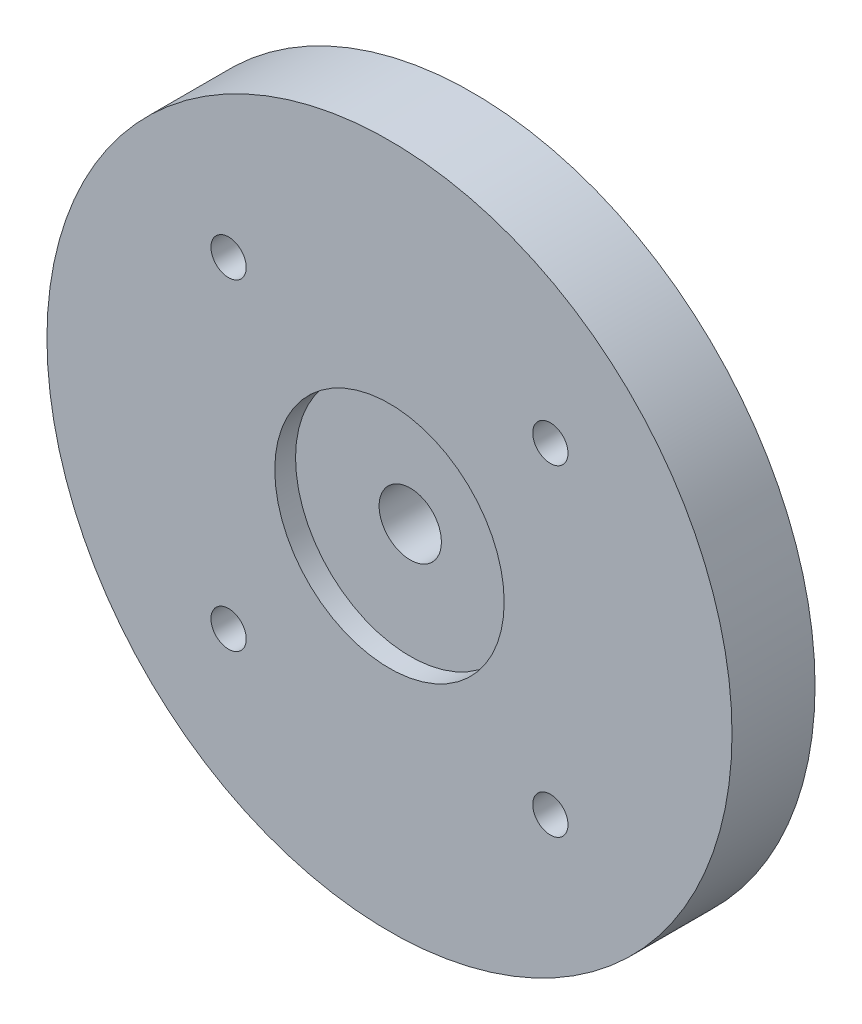
SolidWorks part; units mm, degrees
ref_plane "Front Plane" through (0, 0, 0) normal (0, 0, 1) x (1, 0, 0)
ref_plane "Top Plane" through (0, 0, 0) normal (0, 1, 0) x (1, 0, 0)
ref_plane "Right Plane" through (0, 0, 0) normal (1, 0, 0) x (0, 0, -1)
sketch "Sketch2" plane through (0, 0, 0) normal (0, 0, 1) x (1, 0, 0)
  circle A0 centre (0, 0) radius 33
  dimension "D1" = 66
extrude "Boss-Extrude1" add sketch "Sketch2" along normal blind 8
sketch "Sketch6" plane through (0, 0, 0) normal (0, 0, -1) x (-1, 0, 0)
  circle A0 centre (0, 0) radius 10
  dimension "D1" = 20
extrude "Boss-Extrude2" add sketch "Sketch6" along normal blind 2
sketch "Sketch3" plane through (0, 0, 8) normal (0, 0, 1) x (1, 0, 0)
  line L0 (0, -15.5) -> (0, 15.5) construction
  line L1 (15.5, 15.5) -> (-15.5, 15.5) construction
  line L2 (15.5, -15.5) -> (-15.5, -15.5) construction
  circle A0 centre (-15.5, 15.5) radius 1.7
  circle A1 centre (15.5, 15.5) radius 1.7
  circle A2 centre (15.5, -15.5) radius 1.7
  circle A3 centre (-15.5, -15.5) radius 1.7
  circle A4 centre (0, 0) radius 3
  point P12 (0, 0)
  point P16 (0, 15.5)
  point P19 (0, -15.5)
  dimension "D1" = 3.4
  dimension "D2" = 3.4
  dimension "D3" = 3.4
  dimension "D4" = 3.4
  dimension "D8" = 6
  dimension "D5" = 31
  dimension "D6" = 31
  dimension "D7" = 31
extrude "Cut-Extrude1" cut sketch "Sketch3" against normal through all both and the other way through all
sketch "Sketch4" plane through (0, 0, 0) normal (0, 0, -1) x (-1, 0, 0)
  circle A0 centre (-15.5, 15.5) radius 2.8
  circle A1 centre (15.5, 15.5) radius 2.8
  circle A2 centre (15.5, -15.5) radius 2.8
  circle A3 centre (-15.5, -15.5) radius 2.8
  dimension "D1" = 5.6
  dimension "D2" = 5.6
  dimension "D3" = 5.6
  dimension "D4" = 5.6
extrude "Cut-Extrude2" cut sketch "Sketch4" against normal blind 2 and the other way through all
sketch "Sketch5" plane through (0, 0, 0) normal (0, 0, -1) x (-1, 0, 0)
  circle A0 centre (0, 29.5) radius 2.1
  circle A1 centre (29.5, 0) radius 2.1
  circle A2 centre (0, -29.5) radius 2.1
  circle A3 centre (-29.5, 0) radius 2.1
  point P19 (0, 0)
  dimension "D1" = 4.2
  dimension "D2" = 29.5
  dimension "D3" = 4
extrude "Cut-Extrude3" cut sketch "Sketch5" against normal blind 6
fillet "Fillet1" radius 1 1 edges at (-10, 0, 0)
sketch "Sketch7" plane through (0, 0, 8) normal (0, 0, 1) x (1, 0, 0)
  circle A0 centre (0, 0) radius 11.05
  dimension "D1" = 22.1
extrude "Cut-Extrude4" cut sketch "Sketch7" against normal blind 2
equation "\"N_pins\"= 26"
equation "\"N_lobes\"= \"N_pins\" - 1"
equation "\"R_pc\"= 25"
equation "\"D_pin\"= 3"
equation "\"R_pin\"= \"D_pin\" / 2"
equation "\"ecc\"= 0.72"
equation "\"t_disc\"= 7"
equation "\"N_out\"= 8"
equation "\"D_outc\"=22"
equation "\"D_roller\"= 5"
equation "\"D_outhole\"= \"D_roller\" + 2 * \"ecc\""
equation "\"D_cam_OD\"= 21"
equation "\"D_cam_ID\"= 10"
equation "\"clr_bore\"= 1"
equation "\"D_bore\"= 2 * \"R_pc\" + \"clr_bore\""
equation "\"t_wall\"= 7.5"
equation "\"D_housing\"= \"D_bore\" + 2 * \"t_wall\""
equation "\"D1@Sketch2\"=\"D_housing\""
